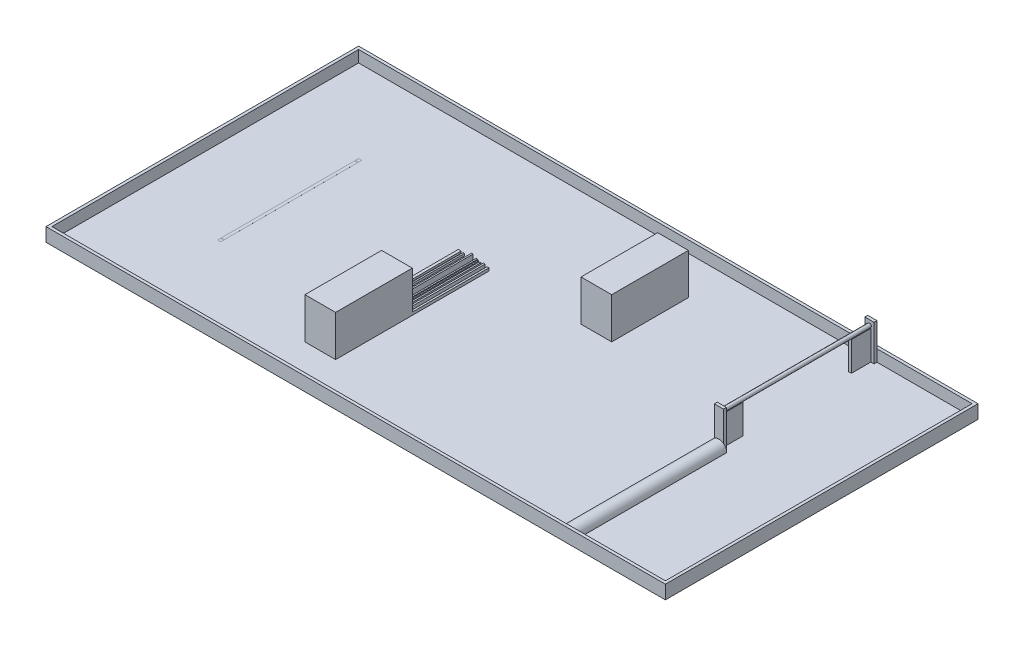
SolidWorks part; units mm, degrees
ref_plane "Front" through (0, 0, 0) normal (0, 0, 1) x (1, 0, 0)
ref_plane "Top" through (0, 0, 0) normal (0, 1, 0) x (1, 0, 0)
ref_plane "Right" through (0, 0, 0) normal (1, 0, 0) x (0, 0, -1)
sketch "Sketch1" plane through (0, 0, 0) normal (0, 1, 0) x (1, 0, 0)
  line L1 (-2000, 1000) -> (2000, 1000)
  line L2 (-2000, 1000) -> (-2000, -1000)
  line L3 (-2000, -1000) -> (2000, -1000)
  line L4 (2000, 1000) -> (2000, -1000)
  line L5 (-2000, 1000) -> (2000, -1000) construction
  line L6 (-2000, -1000) -> (2000, 1000) construction
  point P0 (0, 0)
  dimension "D1" = 4000
  dimension "D2" = 2000
extrude "Boss-Extrude1" add sketch "Sketch1" along normal blind 12.7
sketch "Sketch3" plane through (0, 0, 0) normal (0, -1, 0) x (1, 0, 0)
  line L11 (-2000, 1000) -> (2000, 1000)
  line L12 (-2000, 1000) -> (-2000, -1000)
  line L13 (-2000, -1000) -> (2000, -1000)
  line L14 (2019.05, -1019.05) -> (2019.05, 1019.05)
  line L15 (-2019.05, -1019.05) -> (2019.05, -1019.05)
  line L16 (-2019.05, 1019.05) -> (-2019.05, -1019.05)
  line L17 (2019.05, 1019.05) -> (-2019.05, 1019.05)
  line L18 (2019.05, -1019.05) -> (2019.05, 1019.05)
  line L19 (-2019.05, -1019.05) -> (2019.05, -1019.05)
  line L20 (-2019.05, 1019.05) -> (-2019.05, -1019.05)
  line L21 (2019.05, 1019.05) -> (-2019.05, 1019.05)
  line L22 (2000, 1000) -> (2000, -1000)
  dimension "D1" = 19.05
extrude "Boss-Extrude2" add sketch "Sketch3" against normal blind 88.9
sketch "Sketch4" plane through (0, 12.7, 0) normal (0, 1, 0) x (1, 0, 0)
  line L0 (-1450, 450) -> (-1450, -450) construction
  line L1 (-1460, -460) -> (-1440, -460)
  line L2 (-1460, -460) -> (-1460, -440)
  line L3 (-1460, -440) -> (-1440, -440)
  line L4 (-1440, -460) -> (-1440, -440)
  line L5 (-1460, -460) -> (-1440, -440) construction
  line L6 (-1460, -440) -> (-1440, -460) construction
  line L7 (-1460, 440) -> (-1440, 440)
  line L8 (-1460, 440) -> (-1460, 460)
  line L9 (-1460, 460) -> (-1440, 460)
  line L10 (-1440, 440) -> (-1440, 460)
  line L11 (-1460, 440) -> (-1440, 460) construction
  line L12 (-1460, 460) -> (-1440, 440) construction
  line L13 (-2000, -1000) -> (2000, -1000) construction
  line L14 (-2000, 1000) -> (-2000, -1000) construction
  point P0 (-1450, -450)
  point P5 (-1450, 450)
  dimension "D1" = 900
  dimension "D2" = 550
  dimension "D3" = 550
  dimension "D4" = 20
  dimension "D5" = 20
  dimension "D6" = 20
  dimension "D7" = 20
extrude "Boss-Extrude3" add sketch "Sketch4" along normal blind 0.1
sketch "Sketch5" plane through (0, 12.7, 0) normal (0, 1, 0) x (1, 0, 0)
  line L1 (-1460, -435) -> (-1440, -435)
  line L2 (-1460, -435) -> (-1460, 435)
  line L3 (-1460, 435) -> (-1440, 435)
  line L4 (-1440, -435) -> (-1440, 435)
  line L5 (-1440, -440) -> (-1460, -440) construction
  line L6 (-1460, 440) -> (-1440, 440) construction
  dimension "D1" = 5
  dimension "D2" = 5
extrude "Boss-Extrude4" add sketch "Sketch5" along normal blind 0.1
sketch "Sketch6" plane through (0, 0, 1000) normal (0, 0, -1) x (-1, 0, 0)
  line L0 (2000, 12.7) -> (-2000, 12.7) construction
  line L1 (-1400, 12.7) -> (-1298.4, 12.7)
  arc A0 (-1400, 12.7) -> (-1298.4, 12.7) centre (-1349.2, 12.7) cw
  dimension "D2" = 50.8
  dimension "D3" = 600
  dimension "D1" = 101.6
extrude "Boss-Extrude5" add sketch "Sketch6" along normal blind 1000
sketch "Sketch7" plane through (0, 12.7, 0) normal (0, 1, 0) x (1, 0, 0)
  line L0 (1319.2, 0) -> (1379.2, 0)
  line L2 (1379.2, 0) -> (1379.2, 19.05)
  line L3 (1379.2, 19.05) -> (1319.2, 19.05)
  line L4 (1319.2, 19.05) -> (1319.2, 0)
  line L5 (1349.2, 0) -> (1349.2, 1000) construction
  line L6 (1400, 0) -> (1298.4, 0) construction
  line L7 (2000, 1000) -> (-2000, 1000) construction
  line L8 (1358.725, 19.05) -> (1358.725, 146.05)
  line L9 (1358.725, 146.05) -> (1339.675, 146.05)
  line L10 (1339.675, 146.05) -> (1339.675, 19.05)
  line L11 (1349.2, 500) -> (2000, 500) construction
  line L12 (2000, 1000) -> (2000, -1000) construction
  line L13 (1379.2, 980.95) -> (1319.2, 980.95)
  line L14 (1379.2, 1000) -> (1379.2, 980.95)
  line L15 (1319.2, 1000) -> (1379.2, 1000)
  line L16 (1319.2, 980.95) -> (1319.2, 1000)
  point P3 (1349.2, 0)
  point P17 (1349.2, 146.05)
  line M23 (1298.4, 0) -> (1400, 0)
  line M27 (2000, 1000) -> (-2000, 1000)
  dimension "D1" = 127
  dimension "D2" = 60
  dimension "D3" = 19.05
  dimension "D4" = 19.05
extrude "Boss-Extrude6" add sketch "Sketch7" along normal blind 234.95 contours L3 L4 L2 M23 | L16 L13 L14 M27
sketch "Sketch8" plane through (0, 12.7, 0) normal (0, 1, 0) x (1, 0, 0)
  line L0 (1339.675, 19.05) -> (1358.725, 19.05)
  line L1 (1379.2, 19.05) -> (1319.2, 19.05) construction
  line L2 (1358.725, 19.05) -> (1358.725, 146.05)
  line L3 (1358.725, 146.05) -> (1339.675, 146.05)
  line L4 (1339.675, 146.05) -> (1339.675, 19.05)
  line L7 (2000, 500) -> (1349.2, 500) construction
  line L8 (1358.725, 853.95) -> (1339.675, 853.95)
  line L9 (1358.725, 980.95) -> (1358.725, 853.95)
  line L10 (1339.675, 980.95) -> (1358.725, 980.95)
  line L11 (1339.675, 853.95) -> (1339.675, 980.95)
  point P5 (1349.2, 19.05)
  point P10 (1349.2, 19.05)
  dimension "D1" = 19.05
  dimension "D2" = 127
extrude "Boss-Extrude7" add sketch "Sketch8" along normal blind 190.5
sketch "Sketch9" plane through (0, 0, -980.95) normal (0, 0, 1) x (1, 0, 0)
  line L0 (1358.725, 203.2) -> (1339.675, 203.2) construction
  circle A0 centre (1349.2, 215.7) radius 12.7
  dimension "D1" = 25.4
  dimension "D2" = 12.5
extrude "Boss-Extrude10" add sketch "Sketch9" along normal up to surface (961.9 mm away)
sketch "Sketch10" plane through (0, 12.7, 0) normal (0, 1, 0) x (1, 0, 0)
  line L0 (-2000, -1000) -> (1298.4, -1000) construction
  line L1 (-600, -750) -> (-400, -750)
  line L2 (-600, -750) -> (-600, -250)
  line L3 (-600, -250) -> (-400, -250)
  line L4 (-400, -750) -> (-400, -250)
  line L5 (-2000, -1000) -> (-2000, 1000) construction
  line L6 (-500, -750) -> (-500, -250) construction
  line L7 (200, 750) -> (400, 750)
  line L8 (200, 750) -> (200, 250)
  line L9 (200, 250) -> (400, 250)
  line L10 (400, 750) -> (400, 250)
  line L11 (-600, -500) -> (-400, -500) construction
  line L12 (300, 250) -> (300, 750) construction
  line L13 (400, 500) -> (200, 500) construction
  point P20 (300, 500)
  point P21 (-500, -500)
  dimension "D1" = 200
  dimension "D2" = 500
  dimension "D3" = 250
  dimension "D4" = 1400
  dimension "D5" = 200
  dimension "D6" = 500
  dimension "D7" = 1000
  dimension "D8" = 800
extrude "Boss-Extrude11" add sketch "Sketch10" along normal blind 266.7
sketch "Sketch11" plane through (0, 0, 250) normal (0, 0, -1) x (-1, 0, 0)
  line L0 (400, 12.7) -> (600, 12.7)
  line L1 (500, 12.7) -> (500, 57.15) construction
  line L2 (400, 12.7) -> (400, 31.3608)
  line L3 (400, 279.4) -> (400, 12.7) construction
  line L4 (400, 31.3608) -> (412.4623, 31.3608)
  line L5 (412.4623, 31.3608) -> (412.4623, 19.242)
  line L6 (412.4623, 19.242) -> (424.9476, 19.242)
  line L7 (424.9476, 19.242) -> (424.9476, 40.0176)
  line L8 (424.9476, 40.0176) -> (436.1705, 40.0176)
  line L9 (436.1705, 40.0176) -> (436.1705, 16.6857)
  line L10 (436.1705, 16.6857) -> (451.9691, 16.6857)
  line L11 (451.9691, 16.6857) -> (451.9691, 33.7867)
  line L12 (451.9691, 33.7867) -> (460.3046, 33.7867)
  line L13 (460.3046, 33.7867) -> (460.3046, 29.6298)
  line L14 (460.3046, 29.6298) -> (467.2888, 29.6298)
  line L15 (467.2888, 29.6298) -> (467.2888, 36.3543)
  line L16 (467.2888, 36.3543) -> (474.7329, 36.3543)
  line L17 (474.7329, 36.3543) -> (474.7329, 42.4473)
  line L18 (474.7329, 42.4473) -> (484.0252, 42.4473)
  line L19 (484.0252, 42.4473) -> (484.0252, 22.0304)
  line L20 (484.0252, 22.0304) -> (503.4491, 22.0304)
  line L21 (503.4491, 22.0304) -> (503.4491, 57.15)
  line L22 (503.4491, 57.15) -> (513.4358, 57.15)
  line L23 (513.4358, 57.15) -> (513.4358, 42.4473)
  line L24 (513.4358, 42.4473) -> (523.0834, 42.4473)
  line L25 (523.0834, 42.4473) -> (523.0834, 29.6298)
  line L26 (523.0834, 29.6298) -> (534.1747, 29.6298)
  line L27 (534.1747, 29.6298) -> (534.1747, 22.0304)
  line L28 (534.1747, 22.0304) -> (547.0472, 22.0304)
  line L29 (547.0472, 22.0304) -> (547.0472, 17.687)
  line L30 (547.0472, 17.687) -> (559.6487, 17.687)
  line L31 (559.6487, 17.687) -> (559.6487, 32.2389)
  line L32 (559.6487, 32.2389) -> (569.3802, 32.2389)
  line L33 (569.3802, 32.2389) -> (569.3802, 22.0304)
  line L34 (569.3802, 22.0304) -> (581.7424, 22.0304)
  line L35 (581.7424, 22.0304) -> (581.7424, 34.925)
  line L36 (581.7424, 34.925) -> (600, 34.925)
  line L37 (600, 279.4) -> (600, 12.7) construction
  line L38 (600, 34.925) -> (600, 12.7)
  dimension "D1" = 44.45
extrude "Boss-Extrude12" add sketch "Sketch11" along normal blind 500
